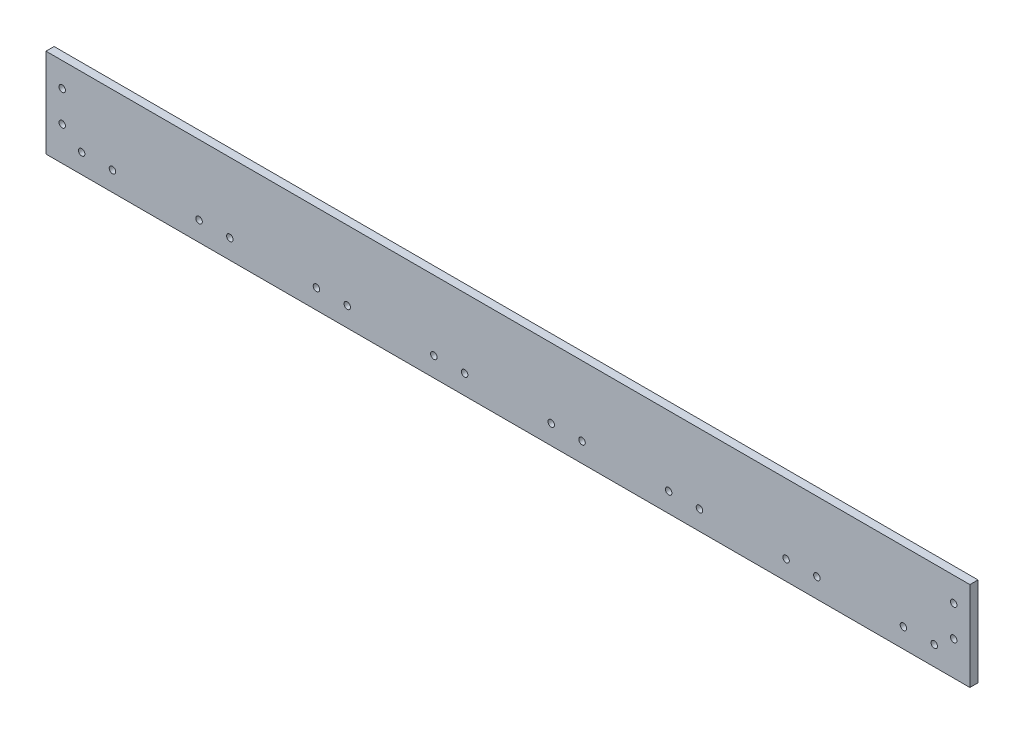
SolidWorks part; units mm, degrees
ref_plane "Front Plane" through (0, 0, 0) normal (0, 0, 1) x (1, 0, 0)
ref_plane "Top Plane" through (0, 0, 0) normal (0, 1, 0) x (1, 0, 0)
ref_plane "Right Plane" through (0, 0, 0) normal (1, 0, 0) x (0, 0, -1)
sketch "Sketch1" plane through (0, 0, 0) normal (0, 0, 1) x (1, 0, 0)
  line L1 (0, 0) -> (723.9, 0)
  line L2 (0, 0) -> (0, 69.85)
  line L3 (0, 69.85) -> (723.9, 69.85)
  line L4 (723.9, 0) -> (723.9, 69.85)
  dimension "D1" = 69.85
  dimension "D2" = 723.9
extrude "Boss-Extrude1" add sketch "Sketch1" along normal blind 6.35
sketch "Sketch2" plane through (0, 0, 6.35) normal (0, 0, 1) x (1, 0, 0)
  line L0 (27.94, 0) -> (27.94, 12.7) construction
  line L2 (0, 15.24) -> (25.4, 15.24) construction
  line L3 (0, 69.85) -> (0, 0) construction
  line L4 (0, 0) -> (723.9, 0) construction
  line L5 (30.48, 15.24) -> (49.53, 15.24) construction
  circle A0 centre (27.94, 15.24) radius 2.54
  circle A1 centre (52.07, 15.24) radius 2.54
  point P13 (1219.2, 76.2)
  dimension "D2" = 5.08
  dimension "D1" = 5.08
  dimension "D3" = 19.05
  dimension "D5" = 12.7
  dimension "D4" = 25.4
extrude "Cut-Extrude1" cut sketch "Sketch2" against normal up to surface (6.35 mm away) contours A1 | A0 up to face at (361.95, 34.925, 0)
sketch "Sketch3" plane through (0, 0, 6.35) normal (0, 0, 1) x (1, 0, 0)
  line L0 (0, 69.85) -> (0, 0) construction
  line L1 (723.9, 69.85) -> (0, 69.85) construction
  line L2 (12.7, 38.735) -> (0, 38.735) construction
  line L3 (12.7, 48.26) -> (12.7, 29.21) construction
  line L4 (0, 38.735) -> (0, 34.925) construction
  line L5 (361.95, 69.85) -> (361.95, 0) construction
  line L6 (0, 0) -> (723.9, 0) construction
  circle A0 centre (12.7, 26.67) radius 2.54
  circle A1 centre (12.7, 50.8) radius 2.54
  circle A2 centre (711.2, 26.67) radius 2.54
  circle A3 centre (711.2, 50.8) radius 2.54
  point P13 (0, 34.925)
  point P15 (361.95, 69.85)
  point P17 (12.7, 38.735)
  point P27 (12.7, 38.735)
  dimension "D2" = 5.08
  dimension "D1" = 5.08
  dimension "D3" = 19.05
  dimension "D4" = 12.7
  dimension "D5" = 3.81
extrude "Cut-Extrude2" cut sketch "Sketch3" against normal up to surface (6.35 mm away) up to face at (25.4, 15.24, 0)
pattern_linear "LPattern2" count 8 spacing 91.9843 along (1, 0, 0) of "Cut-Extrude1"
equation "\"vertical-component-width\"= \"railing-width\" - \"railing-padding\""
equation "\"vertical-component-height\"= 2.75in"
equation "\"material-thickness\"= .25in"
equation "\"D1@Sketch1\"=\"vertical-component-height\""
equation "\"D2@Sketch1\"=\"vertical-component-width\""
equation "\"D1@Boss-Extrude1\"=\"material-thickness\""
equation "\"mounting-hole-diameter\"= .2"
equation "\"mounting-hole-pair-left-to-mount-edge-left\"= 1in"
equation "\"mounting-hole-bottom-to-mount-edge-bottom\"= .5in"
equation "\"mounting-hole-pair-distance-between-holes\"= .75in"
equation "\"distance-between-mounting-hole-pairs\"= ( \"vertical-component-width\" - 2 * \"mounting-hole-pair-left-to-mount-edge-left\" - \"num-mounting-hole-pairs\" * ( 2 * \"mounting-hole-diameter\" + \"mounting-hole-pair-distance-between-holes\" ) ) / ( \"num-mounting-hole-pairs\" - 1 )"
equation "\"num-mounting-hole-pairs\"= 8"
equation "\"D3@Sketch2\"=\"mounting-hole-pair-distance-between-holes\""
equation "\"D5@Sketch2\"=\"mounting-hole-bottom-to-mount-edge-bottom\""
equation "\"D4@Sketch2\"=\"mounting-hole-pair-left-to-mount-edge-left\""
equation "\"D3@LPattern2\"=\"mounting-hole-pair-left-to-next-mounting-hole-pair-left\""
equation "\"D2@Sketch2\"=\"mounting-hole-diameter\""
equation "\"D1@Sketch2\"=\"mounting-hole-diameter\""
equation "\"mounting-hole-pair-left-to-next-mounting-hole-pair-left\"= \"distance-between-mounting-hole-pairs\" + 2 * \"mounting-hole-diameter\" + \"mounting-hole-pair-distance-between-holes\""
equation "\"edge-mounting-hole-pair-inset\"=0.5"
equation "\"D4@Sketch3\"=\"edge-mounting-hole-pair-inset\""
equation "\"edge-mounting-hole-pair-offset-from-mount-vertical-center\"= 0.15"
equation "\"D5@Sketch3\"=\"edge-mounting-hole-pair-offset-from-mount-vertical-center\""
equation "\"D3@Sketch3\"=\"mounting-hole-pair-distance-between-holes\""
equation "\"railing-width\"= 29in"
equation "\"railing-padding\"= .5in"
equation "\"D1@LPattern2\"=\"num-mounting-hole-pairs\""
